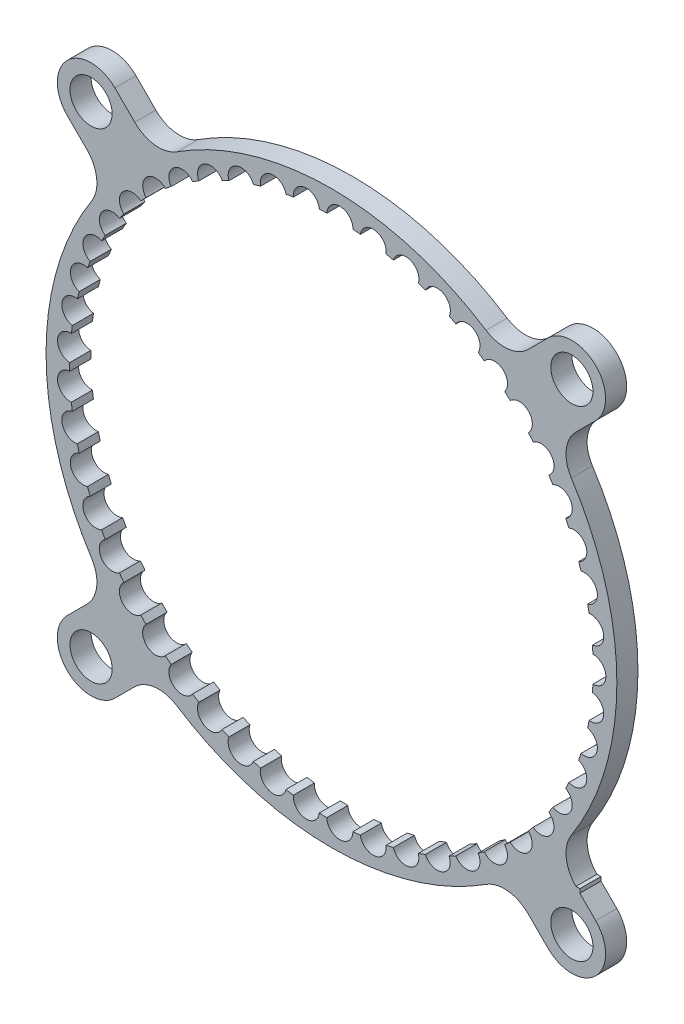
SolidWorks part; units mm, degrees
ref_plane "前视基准面" through (0, 0, 0) normal (0, 0, 1) x (1, 0, 0)
ref_plane "上视基准面" through (0, 0, 0) normal (0, 1, 0) x (1, 0, 0)
ref_plane "右视基准面" through (0, 0, 0) normal (1, 0, 0) x (0, 0, -1)
sketch "草图1" plane through (0, 0, 0) normal (0, 0, 1) x (1, 0, 0)
  line L0 (0, 0) -> (28.5, 0) construction
  line L1 (30.936, 2.4768) -> (30.9988, 1.4996) construction
  line L2 (30.9674, 1.9882) -> (32.4682, 2.0845) construction
  line L3 (30.936, -2.4768) -> (30.9988, -1.4996) construction
  line L4 (30.9674, -1.9882) -> (32.4682, -2.0845) construction
  line L5 (30.9674, -1.9882) -> (30.9956, -1.5491)
  line L6 (30.9674, 1.9882) -> (30.9962, 1.5394)
  line L7 (30.4589, -5.9319) -> (30.543, -5.5)
  line L8 (30.9674, -1.9882) -> (30.9386, -2.4369)
  line L9 (29.4503, -9.7782) -> (29.5889, -9.3606)
  line L10 (30.4589, -5.9319) -> (30.3729, -6.3732)
  line L11 (27.9581, -13.4639) -> (28.149, -13.0675)
  line L12 (29.4503, -9.7782) -> (29.3086, -10.2049)
  line L13 (26.0068, -16.9286) -> (26.2469, -16.5598)
  line L14 (27.9581, -13.4639) -> (27.763, -13.869)
  line L15 (23.6285, -20.1153) -> (23.9138, -19.7802)
  line L16 (26.0068, -16.9286) -> (25.7615, -17.3054)
  line L17 (20.8623, -22.9717) -> (21.188, -22.6759)
  line L18 (23.6285, -20.1153) -> (23.337, -20.4577)
  line L19 (17.7534, -25.4509) -> (18.1143, -25.1991)
  line L20 (20.8623, -22.9717) -> (20.5294, -23.274)
  line L21 (14.3531, -27.5122) -> (14.7432, -27.3087)
  line L22 (17.7534, -25.4509) -> (17.3846, -25.7081)
  line L23 (10.7171, -29.1217) -> (11.13, -28.9698)
  line L24 (14.3531, -27.5122) -> (13.9544, -27.7202)
  line L25 (6.9051, -30.2531) -> (7.334, -30.1552)
  line L26 (10.7171, -29.1217) -> (10.2951, -29.277)
  line L27 (2.9797, -30.8877) -> (3.4177, -30.8455)
  line L28 (6.9051, -30.2531) -> (6.4667, -30.3532)
  line L29 (-0.9946, -31.0152) -> (-0.5548, -31.0293)
  line L30 (2.9797, -30.8877) -> (2.5321, -30.9309)
  line L31 (-4.9526, -30.6334) -> (-4.5182, -30.7036)
  line L32 (-0.9946, -31.0152) -> (-1.444, -31.0008)
  line L33 (-8.8292, -29.7486) -> (-8.4074, -29.8737)
  line L34 (-4.9526, -30.6334) -> (-5.3965, -30.5616)
  line L35 (-12.5609, -28.3753) -> (-12.1585, -28.5534)
  line L36 (-8.8292, -29.7486) -> (-9.2603, -29.6206)
  line L37 (-16.0863, -26.5361) -> (-15.71, -26.7641)
  line L38 (-12.5609, -28.3753) -> (-12.9721, -28.1932)
  line L39 (-19.3476, -24.2611) -> (-19.0036, -24.5355)
  line L40 (-16.0863, -26.5361) -> (-16.4708, -26.3029)
  line L41 (-22.2912, -21.5878) -> (-21.9851, -21.9039)
  line L42 (-19.3476, -24.2611) -> (-19.6992, -23.9808)
  line L43 (-24.8688, -18.5601) -> (-24.6056, -18.9127)
  line L44 (-22.2912, -21.5878) -> (-22.604, -21.2648)
  line L45 (-27.038, -15.2275) -> (-26.8221, -15.6109)
  line L46 (-24.8688, -18.5601) -> (-25.1377, -18.1997)
  line L47 (-28.7633, -11.645) -> (-28.5982, -12.0528)
  line L48 (-27.038, -15.2275) -> (-27.2587, -14.8357)
  line L49 (-30.0163, -7.8712) -> (-29.9047, -8.2968)
  line L50 (-28.7633, -11.645) -> (-28.932, -11.2282)
  line L51 (-30.7764, -3.9682) -> (-30.7201, -4.4046)
  line L52 (-30.0163, -7.8712) -> (-30.1303, -7.4362)
  line L53 (-31.0311, 0) -> (-31.0311, -0.44)
  line L54 (-30.7764, -3.9682) -> (-30.8339, -3.5222)
  line L55 (-30.7764, 3.9682) -> (-30.8326, 3.5318)
  line L56 (-31.0311, 0) -> (-31.0311, 0.4497)
  line L57 (-30.0163, 7.8712) -> (-30.1279, 7.4456)
  line L58 (-30.7764, 3.9682) -> (-30.7189, 4.4142)
  line L59 (-28.7633, 11.645) -> (-28.9284, 11.2371)
  line L60 (-30.0163, 7.8712) -> (-29.9022, 8.3062)
  line L61 (-27.038, 15.2275) -> (-27.2539, 14.8441)
  line L62 (-28.7633, 11.645) -> (-28.5945, 12.0618)
  line L63 (-24.8688, 18.5601) -> (-25.1319, 18.2074)
  line L64 (-27.038, 15.2275) -> (-26.8173, 15.6193)
  line L65 (-22.2912, 21.5878) -> (-22.5973, 21.2717)
  line L66 (-24.8688, 18.5601) -> (-24.5998, 18.9204)
  line L67 (-19.3476, 24.2611) -> (-19.6916, 23.9868)
  line L68 (-22.2912, 21.5878) -> (-21.9784, 21.9108)
  line L69 (-16.0863, 26.5361) -> (-16.4626, 26.308)
  line L70 (-19.3476, 24.2611) -> (-18.996, 24.5415)
  line L71 (-12.5609, 28.3753) -> (-12.9632, 28.1972)
  line L72 (-16.0863, 26.5361) -> (-15.7018, 26.7692)
  line L73 (-8.8292, 29.7486) -> (-9.251, 29.6234)
  line L74 (-12.5609, 28.3753) -> (-12.1497, 28.5573)
  line L75 (-4.9526, 30.6334) -> (-5.3869, 30.5631)
  line L76 (-8.8292, 29.7486) -> (-8.3981, 29.8765)
  line L77 (-0.9946, 31.0152) -> (-1.4344, 31.0011)
  line L78 (-4.9526, 30.6334) -> (-4.5087, 30.7051)
  line L79 (2.9797, 30.8877) -> (2.5417, 30.93)
  line L80 (-0.9946, 31.0152) -> (-0.5452, 31.0296)
  line L81 (6.9051, 30.2531) -> (6.4761, 30.351)
  line L82 (2.9797, 30.8877) -> (3.4273, 30.8446)
  line L83 (10.7171, 29.1217) -> (10.3041, 29.2737)
  line L84 (6.9051, 30.2531) -> (7.3435, 30.1531)
  line L85 (14.3531, 27.5122) -> (13.963, 27.7157)
  line L86 (10.7171, 29.1217) -> (11.1391, 28.9664)
  line L87 (17.7534, 25.4509) -> (17.3926, 25.7026)
  line L88 (14.3531, 27.5122) -> (14.7518, 27.3042)
  line L89 (20.8623, 22.9717) -> (20.5365, 23.2675)
  line L90 (17.7534, 25.4509) -> (18.1222, 25.1936)
  line L91 (23.6285, 20.1153) -> (23.3433, 20.4503)
  line L92 (20.8623, 22.9717) -> (21.1951, 22.6694)
  line L93 (26.0068, 16.9286) -> (25.7668, 17.2973)
  line L94 (23.6285, 20.1153) -> (23.92, 19.7729)
  line L95 (27.9581, 13.4639) -> (27.7672, 13.8603)
  line L96 (26.0068, 16.9286) -> (26.2521, 16.5517)
  line L97 (29.4503, 9.7782) -> (29.3116, 10.1958)
  line L98 (27.9581, 13.4639) -> (28.1532, 13.0588)
  line L99 (30.4589, 5.9319) -> (30.3748, 6.3638)
  line L100 (29.4503, 9.7782) -> (29.592, 9.3514)
  line L101 (30.9674, 1.9882) -> (30.9392, 2.4273)
  line L102 (30.4589, 5.9319) -> (30.5449, 5.4905)
  line L103 (0, 0) -> (0, -23.55) construction
  line L104 (28.4997, -28.4997) -> (33.4495, -23.55) construction
  line L118 (0, -23.55) -> (23.55, -23.55) construction
  line L119 (23.55, -23.55) -> (28.4997, -28.4997) construction
  line L120 (33.4495, -23.55) -> (24.8719, -32.1276) construction
  line L124 (25.6713, -31.3282) -> (23.3201, -28.9769)
  line L126 (-31.3282, -25.6713) -> (-28.9769, -23.3201)
  line L127 (-25.6713, -31.3282) -> (-23.3201, -28.9769)
  line L128 (-25.6713, 31.3282) -> (-23.3201, 28.9769)
  line L129 (-31.3282, 25.6713) -> (-28.9769, 23.3201)
  line L130 (31.3282, 25.6713) -> (28.9769, 23.3201)
  line L131 (25.6713, 31.3282) -> (23.3201, 28.9769)
  line L132 (28.9769, -23.3201) -> (29.4503, -23.3201)
  line L133 (29.4503, -23.3201) -> (29.4503, -23.7934)
  line L134 (29.4503, -23.7934) -> (31.3282, -25.6713)
  circle A1 centre (0, 0) radius 32.535 construction
  circle A2 centre (31.035, 0) radius 1.5 construction
  circle A3 centre (30.7802, -3.9687) radius 1.5 construction
  circle A4 centre (30.02, -7.8722) radius 1.5 construction
  circle A5 centre (28.7669, -11.6464) radius 1.5 construction
  circle A6 centre (27.0414, -15.2294) radius 1.5 construction
  circle A7 centre (24.8719, -18.5624) radius 1.5 construction
  circle A8 centre (22.294, -21.5905) radius 1.5 construction
  circle A9 centre (19.35, -24.2641) radius 1.5 construction
  circle A10 centre (16.0883, -26.5394) radius 1.5 construction
  circle A11 centre (12.5625, -28.3788) radius 1.5 construction
  circle A12 centre (8.8303, -29.7523) radius 1.5 construction
  circle A13 centre (4.9532, -30.6372) radius 1.5 construction
  circle A14 centre (0.9947, -31.0191) radius 1.5 construction
  circle A15 centre (-2.9801, -30.8916) radius 1.5 construction
  circle A16 centre (-6.9059, -30.2569) radius 1.5 construction
  circle A17 centre (-10.7184, -29.1254) radius 1.5 construction
  circle A18 centre (-14.3549, -27.5156) radius 1.5 construction
  circle A19 centre (-17.7556, -25.454) radius 1.5 construction
  circle A20 centre (-20.8649, -22.9745) radius 1.5 construction
  circle A21 centre (-23.6315, -20.1178) radius 1.5 construction
  circle A22 centre (-26.0101, -16.9307) radius 1.5 construction
  circle A23 centre (-27.9616, -13.4656) radius 1.5 construction
  circle A24 centre (-29.4539, -9.7794) radius 1.5 construction
  circle A25 centre (-30.4627, -5.9326) radius 1.5 construction
  circle A26 centre (-30.9712, -1.9884) radius 1.5 construction
  circle A27 centre (-30.9712, 1.9884) radius 1.5 construction
  circle A28 centre (-30.4627, 5.9326) radius 1.5 construction
  circle A29 centre (-29.4539, 9.7794) radius 1.5 construction
  circle A30 centre (-27.9616, 13.4656) radius 1.5 construction
  circle A31 centre (-26.0101, 16.9307) radius 1.5 construction
  circle A32 centre (-23.6315, 20.1178) radius 1.5 construction
  circle A33 centre (-20.8649, 22.9745) radius 1.5 construction
  circle A34 centre (-17.7556, 25.454) radius 1.5 construction
  circle A35 centre (-14.3549, 27.5156) radius 1.5 construction
  circle A36 centre (-10.7184, 29.1254) radius 1.5 construction
  circle A37 centre (-6.9059, 30.2569) radius 1.5 construction
  circle A38 centre (-2.9801, 30.8916) radius 1.5 construction
  circle A39 centre (0.9947, 31.0191) radius 1.5 construction
  circle A40 centre (4.9532, 30.6372) radius 1.5 construction
  circle A41 centre (8.8303, 29.7523) radius 1.5 construction
  circle A42 centre (12.5625, 28.3788) radius 1.5 construction
  circle A43 centre (16.0883, 26.5394) radius 1.5 construction
  circle A44 centre (19.35, 24.2641) radius 1.5 construction
  circle A45 centre (22.294, 21.5905) radius 1.5 construction
  circle A46 centre (24.8719, 18.5624) radius 1.5 construction
  circle A47 centre (27.0414, 15.2294) radius 1.5 construction
  circle A48 centre (28.7669, 11.6464) radius 1.5 construction
  circle A49 centre (30.02, 7.8722) radius 1.5 construction
  circle A50 centre (30.7802, 3.9687) radius 1.5 construction
  circle A51 centre (0, 0) radius 31.035 construction
  arc A52 (30.9956, -1.5491) -> (32.535, 0) centre (30.9907, -0.0048) ccw
  arc A53 (30.9962, 1.5394) -> (32.535, 0) centre (30.9907, -0.0048) cw
  arc A54 (30.543, -5.5) -> (32.2679, -4.1605) centre (30.7357, -3.9678) ccw
  arc A55 (30.9386, -2.4369) -> (32.2679, -4.1605) centre (30.7357, -3.9678) cw
  arc A56 (29.5889, -9.3606) -> (31.4709, -8.2527) centre (29.976, -7.8656) ccw
  arc A57 (30.3729, -6.3732) -> (31.4709, -8.2527) centre (29.976, -7.8656) cw
  arc A58 (28.149, -13.0675) -> (30.1572, -12.2093) centre (28.724, -11.6343) ccw
  arc A59 (29.3086, -10.2049) -> (30.1572, -12.2093) centre (28.724, -11.6343) cw
  arc A60 (26.2469, -16.5598) -> (28.3484, -15.9655) centre (27.0005, -15.2119) ccw
  arc A61 (27.763, -13.869) -> (28.3484, -15.9655) centre (27.0005, -15.2119) cw
  arc A62 (23.9138, -19.7802) -> (26.074, -19.4595) centre (24.8335, -18.5398) ccw
  arc A63 (25.7615, -17.3054) -> (26.074, -19.4595) centre (24.8335, -18.5398) cw
  arc A64 (21.188, -22.6759) -> (23.3715, -22.634) centre (22.2588, -21.5632) ccw
  arc A65 (23.337, -20.4577) -> (23.3715, -22.634) centre (22.2588, -21.5632) cw
  arc A66 (18.1143, -25.1991) -> (20.2852, -25.4369) centre (19.3186, -24.2325) ccw
  arc A67 (20.5294, -23.274) -> (20.2852, -25.4369) centre (19.3186, -24.2325) cw
  arc A68 (14.7432, -27.3087) -> (16.8659, -27.8221) centre (16.0612, -26.504) ccw
  arc A69 (17.3846, -25.7081) -> (16.8659, -27.8221) centre (16.0612, -26.504) cw
  arc A70 (11.13, -28.9698) -> (13.1696, -29.7504) centre (12.5401, -28.3403) ccw
  arc A71 (13.9544, -27.7202) -> (13.1696, -29.7504) centre (12.5401, -28.3403) cw
  arc A72 (7.334, -30.1552) -> (9.2571, -31.1903) centre (8.8131, -29.7112) ccw
  arc A73 (10.2951, -29.277) -> (9.2571, -31.1903) centre (8.8131, -29.7112) cw
  arc A74 (3.4177, -30.8455) -> (5.1926, -32.118) centre (4.9414, -30.5943) ccw
  arc A75 (6.4667, -30.3532) -> (5.1926, -32.118) centre (4.9414, -30.5943) cw
  arc A76 (-0.5548, -31.0293) -> (1.0428, -32.5183) centre (0.9885, -30.975) ccw
  arc A77 (2.5321, -30.9309) -> (1.0428, -32.5183) centre (0.9885, -30.975) cw
  arc A78 (-4.5182, -30.7036) -> (-3.1241, -32.3847) centre (-2.9806, -30.8471) ccw
  arc A79 (-1.444, -31.0008) -> (-3.1241, -32.3847) centre (-2.9806, -30.8471) cw
  arc A80 (-8.4074, -29.8737) -> (-7.2397, -31.7193) centre (-6.9008, -30.2127) ccw
  arc A81 (-5.3965, -30.5616) -> (-7.2397, -31.7193) centre (-6.9008, -30.2127) cw
  arc A82 (-12.1585, -28.5534) -> (-11.2365, -30.5331) centre (-10.7076, -29.0822) ccw
  arc A83 (-9.2603, -29.6206) -> (-11.2365, -30.5331) centre (-10.7076, -29.0822) cw
  arc A84 (-15.71, -26.7641) -> (-15.0487, -28.8455) centre (-14.3387, -27.4741) ccw
  arc A85 (-12.9721, -28.1932) -> (-15.0487, -28.8455) centre (-14.3387, -27.4741) cw
  arc A86 (-19.0036, -24.5355) -> (-18.6138, -26.6843) centre (-17.7343, -25.415) ccw
  arc A87 (-16.4708, -26.3029) -> (-18.6138, -26.6843) centre (-17.7343, -25.415) cw
  arc A88 (-21.9851, -21.9039) -> (-21.8733, -24.0849) centre (-20.8387, -22.9385) ccw
  arc A89 (-19.6992, -23.9808) -> (-21.8733, -24.0849) centre (-20.8387, -22.9385) cw
  arc A90 (-24.6056, -18.9127) -> (-24.7736, -21.0901) centre (-23.6009, -20.0854) ccw
  arc A91 (-22.604, -21.2648) -> (-24.7736, -21.0901) centre (-23.6009, -20.0854) cw
  arc A92 (-26.8221, -15.6109) -> (-27.2672, -17.749) centre (-25.9756, -16.9025) ccw
  arc A93 (-25.1377, -18.1997) -> (-27.2672, -17.749) centre (-25.9756, -16.9025) cw
  arc A94 (-28.5982, -12.0528) -> (-29.313, -14.1164) centre (-27.9238, -13.442) ccw
  arc A95 (-27.2587, -14.8357) -> (-29.313, -14.1164) centre (-27.9238, -13.442) cw
  arc A96 (-29.9047, -8.2968) -> (-30.8775, -10.252) centre (-29.4135, -9.7609) ccw
  arc A97 (-28.932, -11.2282) -> (-30.8775, -10.252) centre (-29.4135, -9.7609) cw
  arc A98 (-30.7201, -4.4046) -> (-31.935, -6.2193) centre (-30.4202, -5.9194) ccw
  arc A99 (-30.1303, -7.4362) -> (-31.935, -6.2193) centre (-30.4202, -5.9194) cw
  arc A100 (-31.0311, -0.44) -> (-32.4682, -2.0845) centre (-30.9274, -1.9808) ccw
  arc A101 (-30.8339, -3.5222) -> (-32.4682, -2.0845) centre (-30.9274, -1.9808) cw
  arc A102 (-30.8326, 3.5318) -> (-32.4682, 2.0845) centre (-30.9268, 1.9904) ccw
  arc A103 (-31.0311, 0.4497) -> (-32.4682, 2.0845) centre (-30.9268, 1.9904) cw
  arc A104 (-30.1279, 7.4456) -> (-31.935, 6.2193) centre (-30.4183, 5.9289) ccw
  arc A105 (-30.7189, 4.4142) -> (-31.935, 6.2193) centre (-30.4183, 5.9289) cw
  arc A106 (-28.9284, 11.2371) -> (-30.8775, 10.252) centre (-29.4104, 9.77) ccw
  arc A107 (-29.9022, 8.3062) -> (-30.8775, 10.252) centre (-29.4104, 9.77) cw
  arc A108 (-27.2539, 14.8441) -> (-29.313, 14.1164) centre (-27.9196, 13.4507) ccw
  arc A109 (-28.5945, 12.0618) -> (-29.313, 14.1164) centre (-27.9196, 13.4507) cw
  arc A110 (-25.1319, 18.2074) -> (-27.2672, 17.749) centre (-25.9703, 16.9106) ccw
  arc A111 (-26.8173, 15.6193) -> (-27.2672, 17.749) centre (-25.9703, 16.9106) cw
  arc A112 (-22.5973, 21.2717) -> (-24.7736, 21.0901) centre (-23.5947, 20.0928) ccw
  arc A113 (-24.5998, 18.9204) -> (-24.7736, 21.0901) centre (-23.5947, 20.0928) cw
  arc A114 (-19.6916, 23.9868) -> (-21.8733, 24.0849) centre (-20.8315, 22.945) ccw
  arc A115 (-21.9784, 21.9108) -> (-21.8733, 24.0849) centre (-20.8315, 22.945) cw
  arc A116 (-16.4626, 26.308) -> (-18.6138, 26.6843) centre (-17.7264, 25.4205) ccw
  arc A117 (-18.996, 24.5415) -> (-18.6138, 26.6843) centre (-17.7264, 25.4205) cw
  arc A118 (-12.9632, 28.1972) -> (-15.0487, 28.8455) centre (-14.3301, 27.4786) ccw
  arc A119 (-15.7018, 26.7692) -> (-15.0487, 28.8455) centre (-14.3301, 27.4786) cw
  arc A120 (-9.251, 29.6234) -> (-11.2365, 30.5331) centre (-10.6986, 29.0855) ccw
  arc A121 (-12.1497, 28.5573) -> (-11.2365, 30.5331) centre (-10.6986, 29.0855) cw
  arc A122 (-5.3869, 30.5631) -> (-7.2397, 31.7193) centre (-6.8914, 30.2148) ccw
  arc A123 (-8.3981, 29.8765) -> (-7.2397, 31.7193) centre (-6.8914, 30.2148) cw
  arc A124 (-1.4344, 31.0011) -> (-3.1241, 32.3847) centre (-2.971, 30.848) ccw
  arc A125 (-4.5087, 30.7051) -> (-3.1241, 32.3847) centre (-2.971, 30.848) cw
  arc A126 (2.5417, 30.93) -> (1.0428, 32.5183) centre (0.9981, 30.9747) ccw
  arc A127 (-0.5452, 31.0296) -> (1.0428, 32.5183) centre (0.9981, 30.9747) cw
  arc A128 (6.4761, 30.351) -> (5.1926, 32.118) centre (4.9509, 30.5927) ccw
  arc A129 (3.4273, 30.8446) -> (5.1926, 32.118) centre (4.9509, 30.5927) cw
  arc A130 (10.3041, 29.2737) -> (9.2571, 31.1903) centre (8.8223, 29.7085) ccw
  arc A131 (7.3435, 30.1531) -> (9.2571, 31.1903) centre (8.8223, 29.7085) cw
  arc A132 (13.963, 27.7157) -> (13.1696, 29.7504) centre (12.5489, 28.3364) ccw
  arc A133 (11.1391, 28.9664) -> (13.1696, 29.7504) centre (12.5489, 28.3364) cw
  arc A134 (17.3926, 25.7026) -> (16.8659, 27.8221) centre (16.0695, 26.499) ccw
  arc A135 (14.7518, 27.3042) -> (16.8659, 27.8221) centre (16.0695, 26.499) cw
  arc A136 (20.5365, 23.2675) -> (20.2852, 25.4369) centre (19.3262, 24.2265) ccw
  arc A137 (18.1222, 25.1936) -> (20.2852, 25.4369) centre (19.3262, 24.2265) cw
  arc A138 (23.3433, 20.4503) -> (23.3715, 22.634) centre (22.2655, 21.5563) ccw
  arc A139 (21.1951, 22.6694) -> (23.3715, 22.634) centre (22.2655, 21.5563) cw
  arc A140 (25.7668, 17.2973) -> (26.074, 19.4595) centre (24.8393, 18.532) ccw
  arc A141 (23.92, 19.7729) -> (26.074, 19.4595) centre (24.8393, 18.532) cw
  arc A142 (27.7672, 13.8603) -> (28.3484, 15.9655) centre (27.0052, 15.2035) ccw
  arc A143 (26.2521, 16.5517) -> (28.3484, 15.9655) centre (27.0052, 15.2035) cw
  arc A144 (29.3116, 10.1958) -> (30.1572, 12.2093) centre (28.7277, 11.6253) ccw
  arc A145 (28.1532, 13.0588) -> (30.1572, 12.2093) centre (28.7277, 11.6253) cw
  arc A146 (30.3748, 6.3638) -> (31.4709, 8.2527) centre (29.9784, 7.8563) ccw
  arc A147 (29.592, 9.3514) -> (31.4709, 8.2527) centre (29.9784, 7.8563) cw
  arc A148 (30.9392, 2.4273) -> (32.2679, 4.1605) centre (30.7369, 3.9582) ccw
  arc A149 (30.5449, 5.4905) -> (32.2679, 4.1605) centre (30.7369, 3.9582) cw
  circle A168 centre (28.4997, -28.4997) radius 2.5
  circle A197 centre (28.4997, -28.4997) radius 4 construction
  arc A198 (25.6713, -31.3282) -> (31.3282, -25.6713) centre (28.4997, -28.4997) ccw
  arc A199 (-31.3282, -25.6713) -> (-25.6713, -31.3282) centre (-28.4997, -28.4997) ccw
  circle A200 centre (-28.4997, -28.4997) radius 2.5
  arc A208 (-25.6713, 31.3282) -> (-31.3282, 25.6713) centre (-28.4997, 28.4997) ccw
  circle A209 centre (-28.4997, 28.4997) radius 2.5
  arc A210 (31.3282, 25.6713) -> (25.6713, 31.3282) centre (28.4997, 28.4997) ccw
  circle A211 centre (28.4997, 28.4997) radius 2.5
  arc A212 (-18.3252, -28.4428) -> (18.3252, -28.4428) centre (0, 0) ccw
  arc A213 (28.4428, -18.3252) -> (28.4428, 18.3252) centre (0, 0) ccw
  arc A215 (-28.4428, -18.3252) -> (-28.4428, 18.3252) centre (0, 0) cw
  arc A218 (18.3252, 28.4428) -> (-18.3252, 28.4428) centre (0, 0) ccw
  arc A219 (-18.3252, 28.4428) -> (-23.3201, 28.9769) centre (-20.4916, 31.8053) cw
  arc A220 (-28.4428, 18.3252) -> (-28.9769, 23.3201) centre (-31.8053, 20.4916) ccw
  arc A221 (-18.3252, -28.4428) -> (-23.3201, -28.9769) centre (-20.4916, -31.8053) ccw
  arc A222 (-28.4428, -18.3252) -> (-28.9769, -23.3201) centre (-31.8053, -20.4916) cw
  arc A223 (18.3252, -28.4428) -> (23.3201, -28.9769) centre (20.4916, -31.8053) cw
  arc A224 (28.4428, -18.3252) -> (28.9769, -23.3201) centre (31.8053, -20.4916) ccw
  arc A225 (28.4428, 18.3252) -> (28.9769, 23.3201) centre (31.8053, 20.4916) cw
  arc A226 (23.3201, 28.9769) -> (18.3252, 28.4428) centre (20.4916, 31.8053) cw
  point P386 (21.4419, -26.3865)
  point P407 (26.0685, -21.8273)
  point P459 (-28.5, -28.5)
  dimension "D1" = 3
  dimension "D2" = 135
  dimension "D3" = 90
  dimension "D5" = 49
  dimension "D6" = 4
  dimension "D7" = 4
  dimension "D8" = 4
  dimension "D4" = 49
extrude "凸台-拉伸1" add sketch "草图1" along normal blind 2.5
